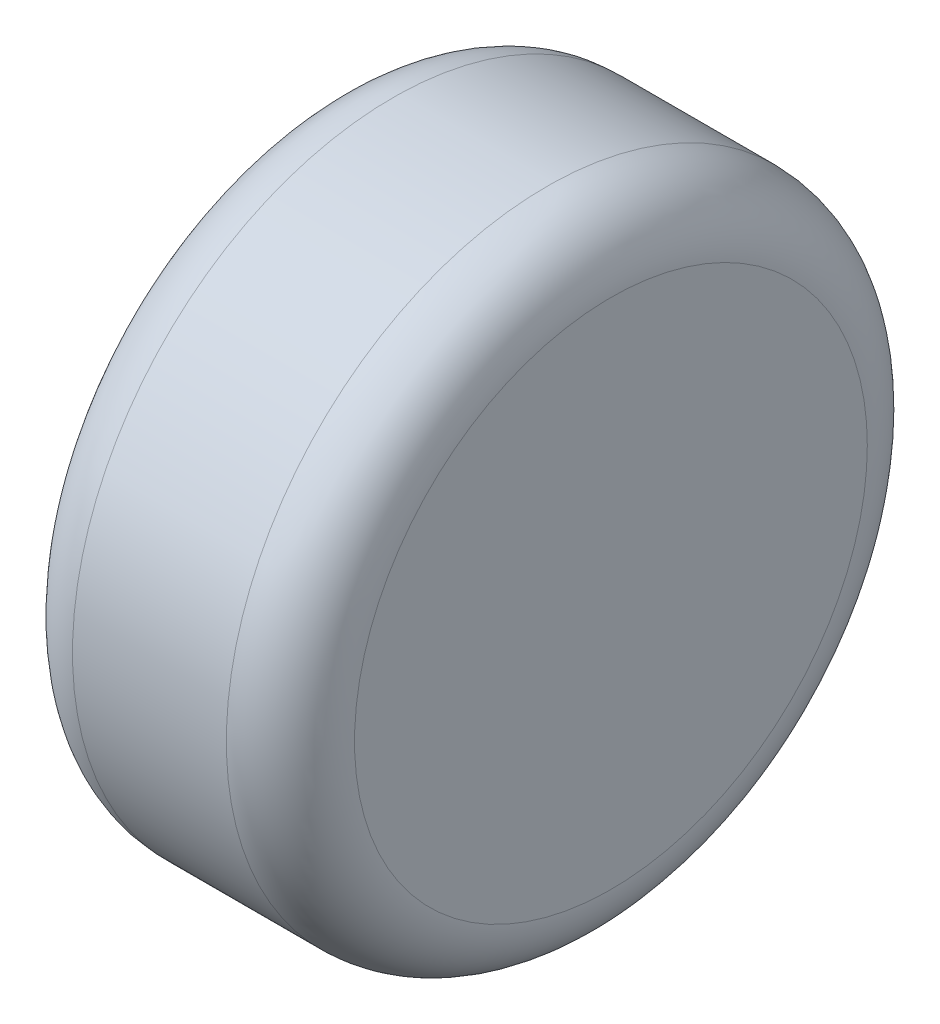
SolidWorks part; units mm, degrees
ref_plane "Front Plane" through (0, 0, 0) normal (0, 0, 1) x (1, 0, 0)
ref_plane "Top Plane" through (0, 0, 0) normal (0, 1, 0) x (1, 0, 0)
ref_plane "Right Plane" through (0, 0, 0) normal (1, 0, 0) x (0, 0, -1)
sketch "Sketch1" plane through (0, 0, 0) normal (1, 0, 0) x (0, 0, -1)
  circle A0 centre (0, 0) radius 63.5
  dimension "D1" = 127
extrude "Boss-Extrude1" add sketch "Sketch1" along normal blind 55.88
fillet "Fillet1" radius 12.7 2 edges at (55.88, 0, -63.5) (0, 0, -63.5)
